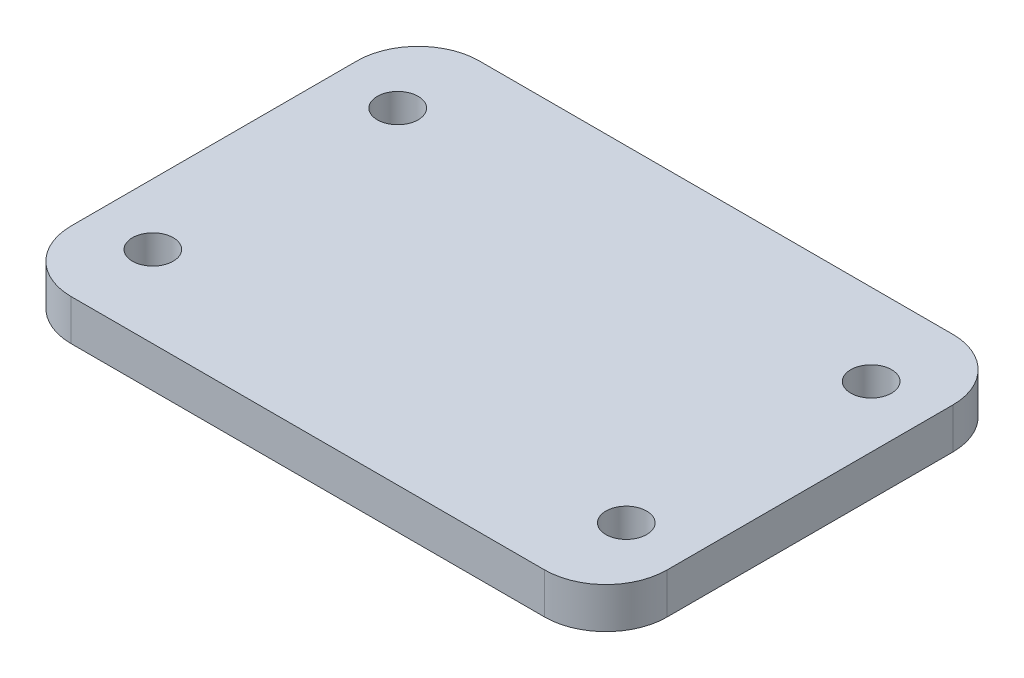
SolidWorks part; units mm, degrees
material "AISI 304"
ref_plane "Front Plane" through (0, 0, 0) normal (0, 0, 1) x (1, 0, 0)
ref_plane "Top Plane" through (0, 0, 0) normal (0, 1, 0) x (1, 0, 0)
ref_plane "Right Plane" through (0, 0, 0) normal (1, 0, 0) x (0, 0, -1)
sketch "Croquis1" plane through (0, 0, 0) normal (0, 1, 0) x (1, 0, 0)
  line L1 (58, -50) -> (-58, -50)
  line L2 (73, -35) -> (73, 35)
  line L3 (58, 50) -> (-58, 50)
  line L4 (-73, -35) -> (-73, 35)
  line L5 (73, -50) -> (-73, 50) construction
  line L6 (73, 50) -> (-73, -50) construction
  arc A0 (73, 35) -> (58, 50) centre (58, 35) ccw
  arc A1 (58, -50) -> (73, -35) centre (58, -35) ccw
  arc A2 (-58, -50) -> (-73, -35) centre (-58, -35) cw
  arc A3 (-58, 50) -> (-73, 35) centre (-58, 35) ccw
  point P0 (0, 0)
  dimension "D3" = 15
  dimension "D1" = 146
  dimension "D2" = 100
extrude "Saliente-Extruir1" add sketch "Croquis1" along normal blind 10
sketch "Croquis2" plane through (0, 10, 0) normal (0, 1, 0) x (1, 0, 0)
  line L0 (58, 50) -> (-58, 50) construction
  line L1 (-73, 35) -> (-73, -35) construction
  circle A0 centre (-58, 30) radius 5
  dimension "D3" = 10
  dimension "D1" = 20
  dimension "D2" = 15
extrude "Cortar-Extruir1" cut sketch "Croquis2" against normal blind 10
pattern_linear "MatrizL1" count 3 spacing 116 along (1, 0, 0) of "Cortar-Extruir1"
pattern_linear "MatrizL2" count 3 spacing 60 along (0, 0, 1) of "MatrizL1", "Cortar-Extruir1"
